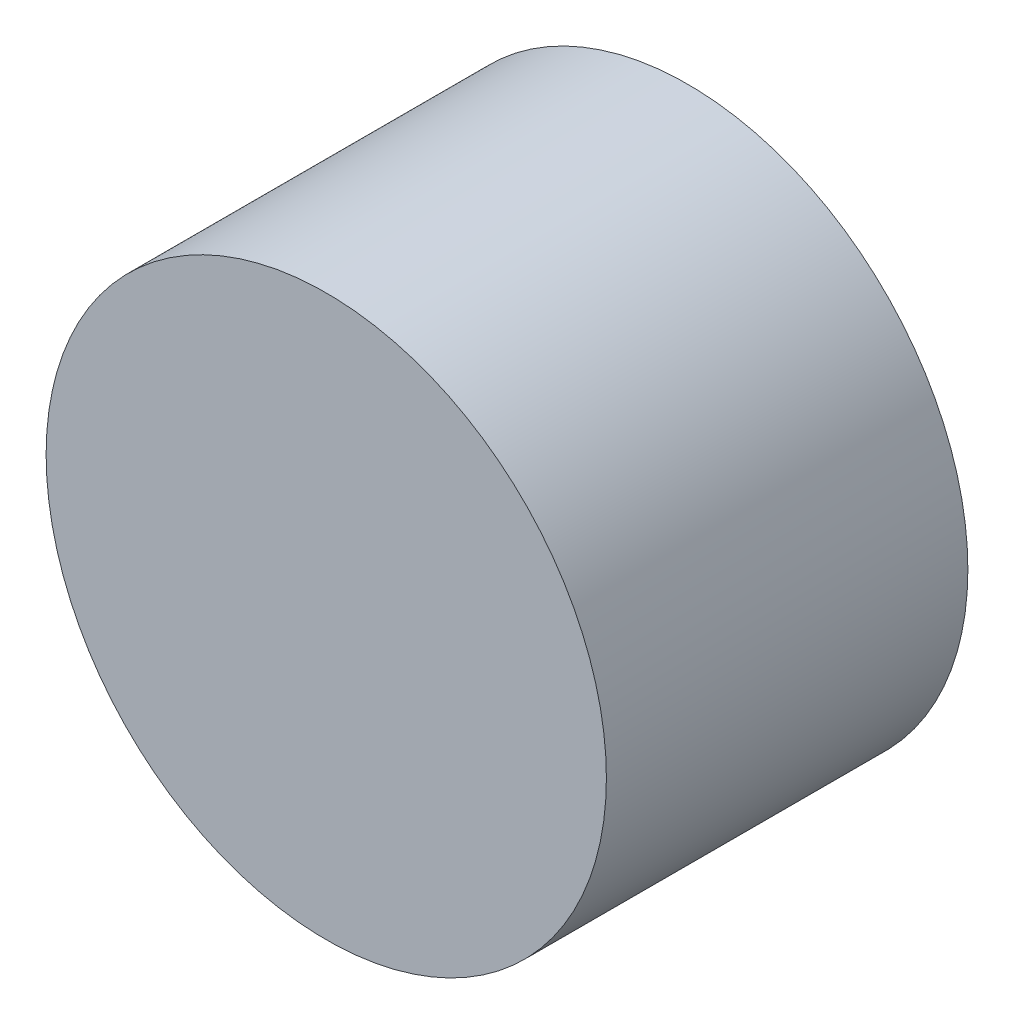
SolidWorks part; units mm, degrees
ref_plane "Plan de face" through (0, 0, 0) normal (0, 0, 1) x (1, 0, 0)
ref_plane "Plan de dessus" through (0, 0, 0) normal (0, 1, 0) x (1, 0, 0)
ref_plane "Plan de droite" through (0, 0, 0) normal (1, 0, 0) x (0, 0, -1)
sketch "Esquisse1" plane through (0, 0, 0) normal (0, 0, 1) x (1, 0, 0)
  circle A0 centre (0, 0) radius 23.25
  dimension "D1" = 46.5
extrude "Boss.-Extru.1" add sketch "Esquisse1" along normal blind 30
